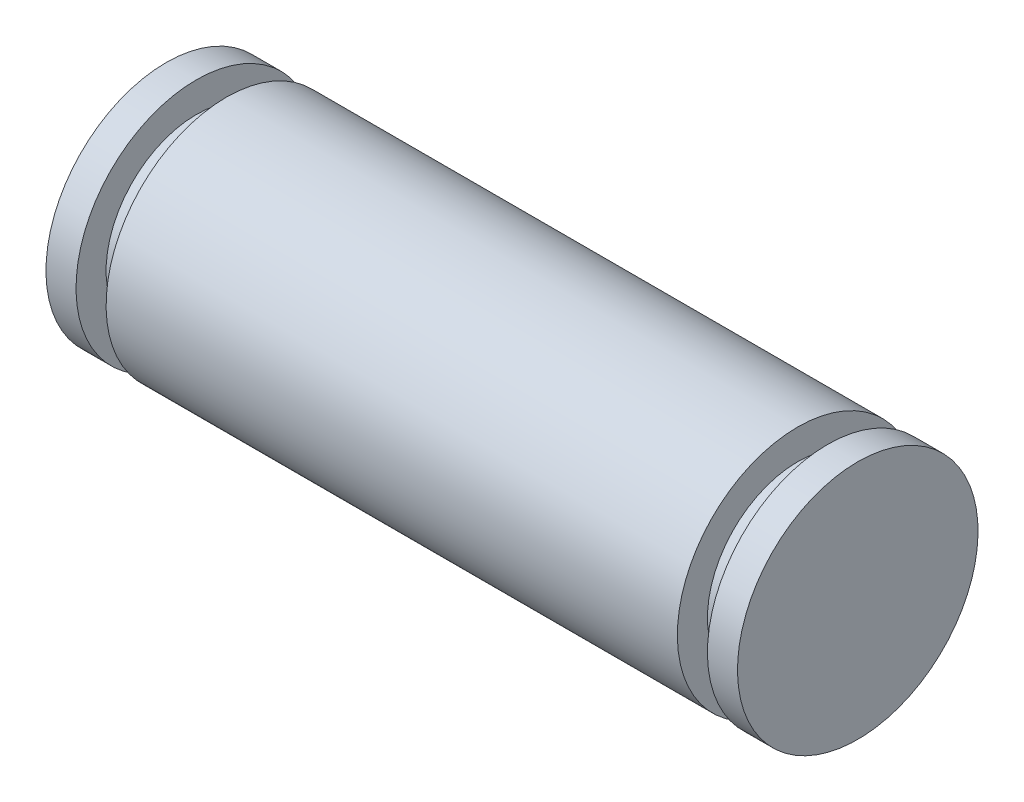
SolidWorks part; units mm, degrees
ref_plane "Plan de face" through (0, 0, 0) normal (0, 0, 1) x (1, 0, 0)
ref_plane "Plan de dessus" through (0, 0, 0) normal (0, 1, 0) x (1, 0, 0)
ref_plane "Plan de droite" through (0, 0, 0) normal (1, 0, 0) x (0, 0, -1)
sketch "Esquisse1" plane through (0, 0, 0) normal (0, 0, 1) x (1, 0, 0)
  line L0 (-11.5, 0) -> (-11.5, 4)
  line L1 (-11.5, 4) -> (-10.5, 4)
  line L2 (-10.5, 4) -> (-10.5, 3)
  line L3 (-10.5, 3) -> (-9.5, 3)
  line L4 (-9.5, 3) -> (-9.5, 4)
  line L5 (-9.5, 4) -> (9.5, 4)
  line L6 (9.5, 4) -> (9.5, 3)
  line L7 (9.5, 3) -> (10.5, 3)
  line L8 (10.5, 3) -> (10.5, 4)
  line L9 (10.5, 4) -> (11.5, 4)
  line L10 (11.5, 4) -> (11.5, 0)
  line L11 (11.5, 0) -> (-11.5, 0)
  point P7 (0, 0)
  dimension "D1" = 19
  dimension "D2" = 1
  dimension "D3" = 1
  dimension "D4" = 4
  dimension "D5" = 1
revolve "Révolution1" add sketch "Esquisse1" angle 360 about L11
